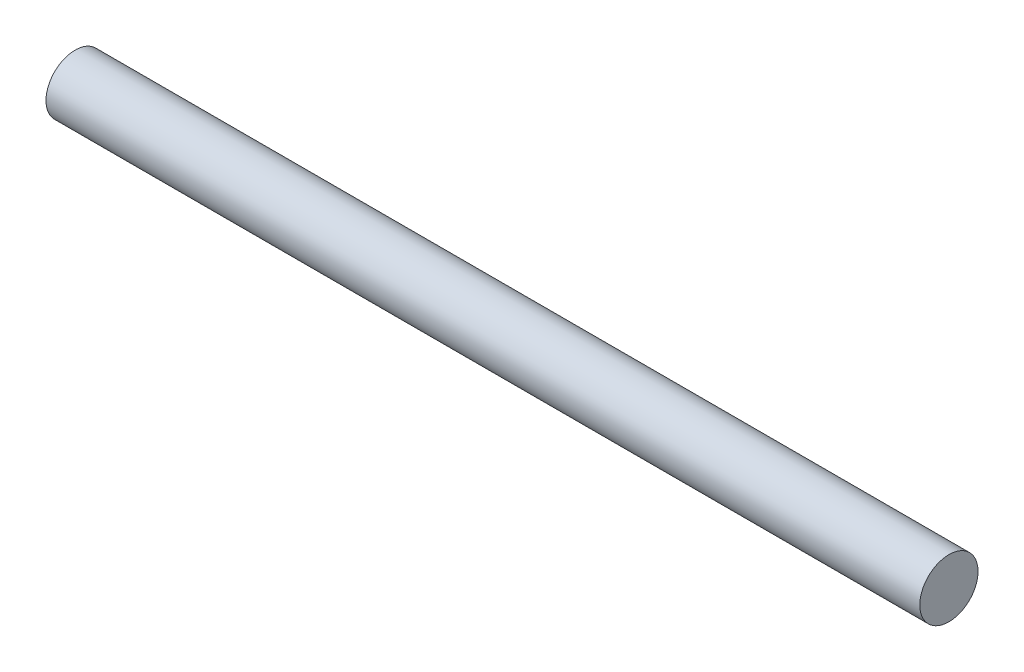
SolidWorks part; units mm, degrees
ref_plane "Front Plane" through (0, 0, 0) normal (0, 0, 1) x (1, 0, 0)
ref_plane "Top Plane" through (0, 0, 0) normal (0, 1, 0) x (1, 0, 0)
ref_plane "Right Plane" through (0, 0, 0) normal (1, 0, 0) x (0, 0, -1)
sketch "Sketch1" plane through (0, 0, 0) normal (1, 0, 0) x (0, 0, -1)
  circle A0 centre (0, 0) radius 3
  dimension "D1" = 6
extrude "Boss-Extrude1" add sketch "Sketch1" along normal blind 90
